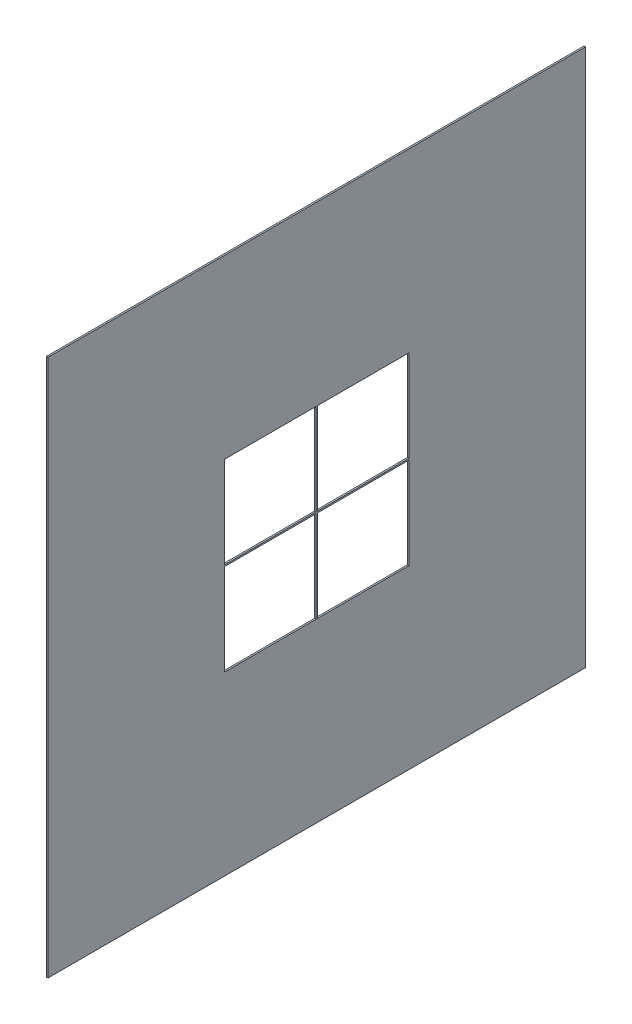
SolidWorks part; units mm, degrees
ref_plane "Front Plane" through (0, 0, 0) normal (0, 0, 1) x (1, 0, 0)
ref_plane "Top Plane" through (0, 0, 0) normal (0, 1, 0) x (1, 0, 0)
ref_plane "Right Plane" through (0, 0, 0) normal (1, 0, 0) x (0, 0, -1)
sketch "Sketch1" plane through (0, 0, 0) normal (1, 0, 0) x (0, 0, -1)
  line L1 (-1750, -1750) -> (1750, -1750)
  line L2 (-1750, -1750) -> (-1750, 1750)
  line L3 (-1750, 1750) -> (1750, 1750)
  line L4 (1750, -1750) -> (1750, 1750)
  line L5 (-1750, -1750) -> (1750, 1750) construction
  line L6 (-1750, 1750) -> (1750, -1750) construction
  point P0 (0, 0)
  dimension "D1" = 3500
  dimension "D2" = 3500
extrude "Boss-Extrude1" add sketch "Sketch1" along normal blind 10
sketch "Sketch2" plane through (10, 0, 0) normal (1, 0, 0) x (0, 0, -1)
  line L0 (0, 600) -> (0, -600) construction
  line L1 (-600, -600) -> (-5, -600)
  line L2 (-600, -600) -> (-600, -5)
  line L3 (-600, 600) -> (-5, 600)
  line L4 (600, -600) -> (600, -5)
  line L5 (-600, -600) -> (600, 600) construction
  line L6 (-600, 600) -> (600, -600) construction
  line L7 (-600, 0) -> (600, 0) construction
  line L8 (-5, 600) -> (-5, 5)
  line L9 (5, 600) -> (5, 5)
  line L10 (-600, -5) -> (-5, -5)
  line L11 (-600, 5) -> (-5, 5)
  line L12 (5, 600) -> (600, 600)
  line L13 (600, 5) -> (600, 600)
  line L14 (-600, 5) -> (-600, 600)
  line L15 (5, -600) -> (600, -600)
  line L16 (-5, -5) -> (-5, -600)
  line L18 (5, 5) -> (600, 5)
  line L19 (-600, 5) -> (600, 5) construction
  line L20 (5, -5) -> (5, -600)
  line L21 (5, 600) -> (5, -600) construction
  line L22 (5, -5) -> (600, -5)
  line L23 (-600, -5) -> (600, -5) construction
  point P0 (0, 0)
  dimension "D1" = 1200
  dimension "D2" = 1200
  dimension "D4" = 5
  dimension "D5" = 5
  dimension "D6" = 5
extrude "Cut-Extrude1" cut sketch "Sketch2" against normal blind 10
